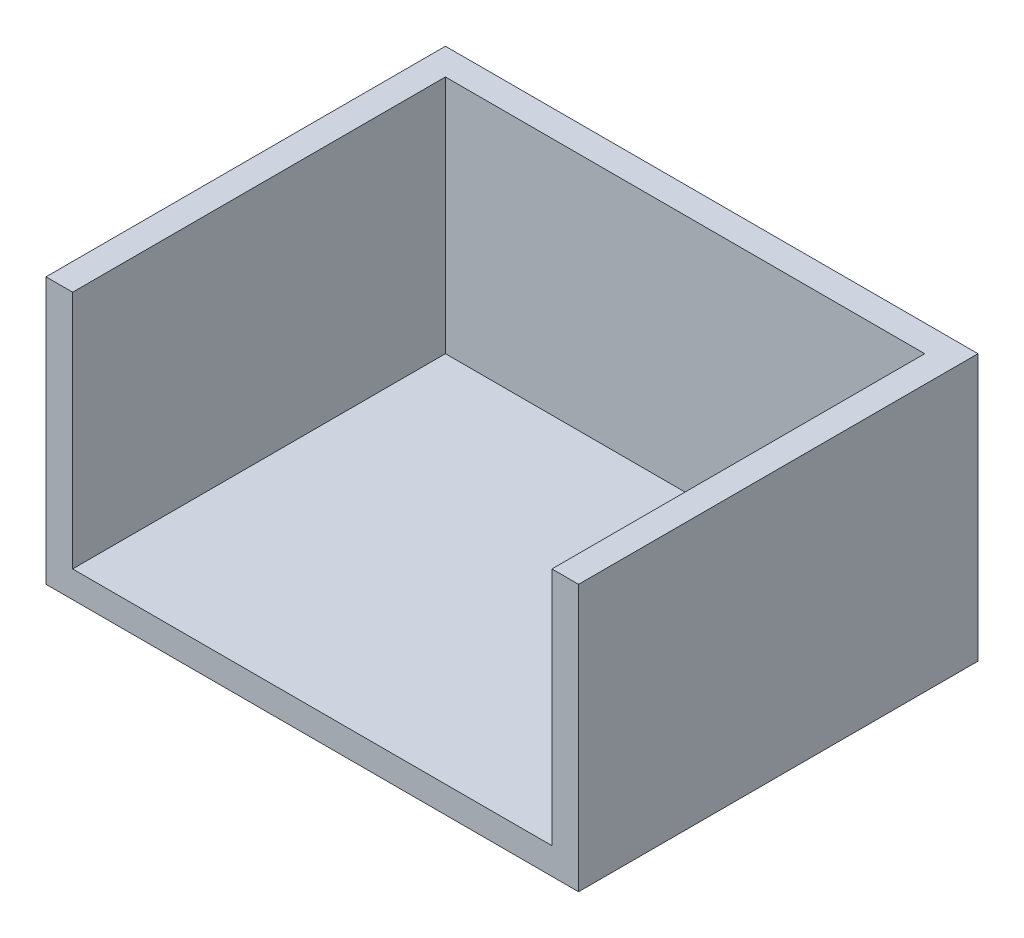
SolidWorks part; units mm, degrees
ref_plane "Front Plane" through (0, 0, 0) normal (0, 0, 1) x (1, 0, 0)
ref_plane "Top Plane" through (0, 0, 0) normal (0, 1, 0) x (1, 0, 0)
ref_plane "Right Plane" through (0, 0, 0) normal (1, 0, 0) x (0, 0, -1)
sketch "Sketch1" plane through (0, 0, 0) normal (0, 1, 0) x (1, 0, 0)
  line L1 (-50.8, 38.1) -> (50.8, 38.1)
  line L2 (-50.8, 38.1) -> (-50.8, -38.1)
  line L3 (-50.8, -38.1) -> (50.8, -38.1)
  line L4 (50.8, 38.1) -> (50.8, -38.1)
  point P4 (0, 38.1)
  point P6 (-50.8, 0)
  dimension "D1" = 76.2
  dimension "D2" = 101.6
extrude "Boss-Extrude1" add sketch "Sketch1" along normal mid plane 50.8
shell "Shell1" thickness 5.08
